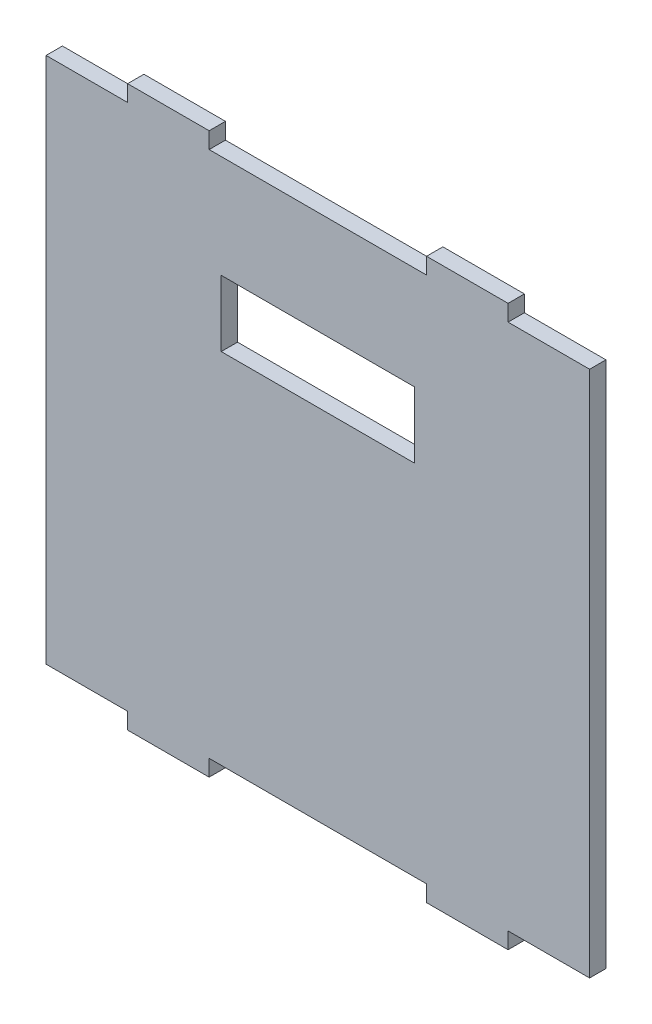
SolidWorks part; units mm, degrees
ref_plane "Plano frontal" through (0, 0, 0) normal (0, 0, 1) x (1, 0, 0)
ref_plane "Plano superior" through (0, 0, 0) normal (0, 1, 0) x (1, 0, 0)
ref_plane "Plano direito" through (0, 0, 0) normal (1, 0, 0) x (0, 0, -1)
sketch "Esboço1" plane through (0, 0, 0) normal (0, 0, 1) x (1, 0, 0)
  line L0 (-70, -97) -> (-100, -97)
  line L2 (-100, 97) -> (-100, -97)
  line L4 (100, 97) -> (100, -97)
  line L5 (-100, 97) -> (100, -97) construction
  line L6 (-100, -97) -> (100, 97) construction
  line L8 (-70, -97) -> (-70, -103)
  line L9 (-70, -103) -> (-40, -103)
  line L10 (-40, -97) -> (-40, -103)
  line L12 (40, -97) -> (40, -103)
  line L13 (40, -103) -> (70, -103)
  line L14 (70, -97) -> (70, -103)
  line L15 (-40, -97) -> (40, -97)
  line L16 (70, -97) -> (100, -97)
  line L17 (100, 97) -> (70, 97)
  line L19 (70, 97) -> (70, 103)
  line L20 (70, 103) -> (40, 103)
  line L21 (40, 97) -> (40, 103)
  line L23 (-40, 97) -> (-40, 103)
  line L24 (-40, 103) -> (-70, 103)
  line L25 (-70, 97) -> (-70, 103)
  line L26 (40, 97) -> (-40, 97)
  line L27 (-70, 97) -> (-100, 97)
  point P0 (0, 0)
  dimension "D1" = 194
  dimension "D2" = 200
  dimension "D3" = 30
  dimension "D4" = 30
  dimension "D5" = 6
  dimension "D6" = 6
  dimension "D7" = 30
  dimension "D8" = 30
  dimension "D9" = 6
  dimension "D10" = 6
  dimension "D11" = 6
  dimension "D12" = 6
  dimension "D13" = 30
  dimension "D14" = 30
  dimension "D15" = 30
  dimension "D16" = 30
  dimension "D17" = 6
  dimension "D18" = 6
extrude "Ressalto-extrusão1" add sketch "Esboço1" along normal blind 6
sketch "Esboço4" plane through (0, 0, 0) normal (0, 0, -1) x (-1, 0, 0)
  line L0 (-100, -97) -> (-100, 97) construction
  line L1 (-35.55, 59.15) -> (35.55, 59.15)
  line L2 (-35.55, 59.15) -> (-35.55, 34.85)
  line L3 (-35.55, 34.85) -> (35.55, 34.85)
  line L4 (35.55, 59.15) -> (35.55, 34.85)
  line L5 (-35.55, 59.15) -> (35.55, 34.85) construction
  line L6 (-35.55, 34.85) -> (35.55, 59.15) construction
  line L7 (-40, -103) -> (-70, -103) construction
  point P0 (0, 47)
  dimension "D1" = 100
  dimension "D2" = 150
  dimension "D3" = 24.3
  dimension "D4" = 71.1
extrude "Corte-extrusão2" cut sketch "Esboço4" against normal blind 6
